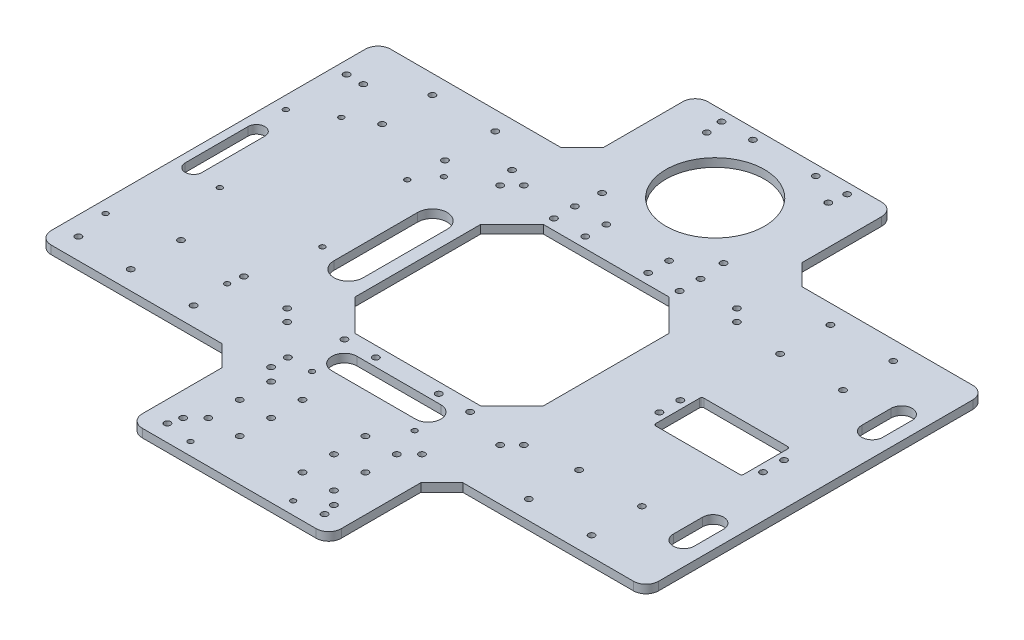
SolidWorks part; units mm, degrees
material "Thornel Mat VMA"
ref_plane "前视基准面" through (0, 0, 0) normal (0, 0, 1) x (1, 0, 0)
ref_plane "上视基准面" through (0, 0, 0) normal (0, 1, 0) x (1, 0, 0)
ref_plane "右视基准面" through (0, 0, 0) normal (1, 0, 0) x (0, 0, -1)
other "Configuration Table"
sketch "草图1" plane through (0, 0, 0) normal (0, 1, 0) x (1, 0, 0)
  line L0 (0, 0) -> (0, 135) construction
  line L1 (-145, -135) -> (145, -135)
  line L2 (-145, -135) -> (-145, 135)
  line L3 (-145, 135) -> (145, 135)
  line L4 (145, -135) -> (145, 135)
  line L5 (-145, -135) -> (145, 135) construction
  line L6 (-145, 135) -> (145, -135) construction
  line L7 (0, 0) -> (145, 0) construction
  line L8 (-47.5, 135) -> (-47.5, 81)
  line L9 (-47.5, 81) -> (-145, 81)
  line L10 (47.5, 81) -> (145, 81)
  line L11 (47.5, 135) -> (47.5, 81)
  line L12 (47.5, -81) -> (145, -81)
  line L13 (47.5, -135) -> (47.5, -81)
  line L14 (-47.5, -81) -> (-145, -81)
  line L15 (-47.5, -135) -> (-47.5, -81)
  point P0 (0, 0)
  dimension "D1" = 290
  dimension "D2" = 270
  dimension "D3" = 162
  dimension "D4" = 95
extrude "凸台-拉伸1" add sketch "草图1" along normal blind 4 contours L15 L1 L13 L12 L4 L10 L11 L3 L8 L9 L2 L14
sketch "草图2" plane through (0, 4, 0) normal (0, 1, 0) x (1, 0, 0)
  line L0 (0, 0) -> (145, 0) construction
  line L1 (145, -81) -> (145, 81) construction
  line L2 (0, 0) -> (0, 135) construction
  line L3 (-47.5, 135) -> (47.5, 135) construction
  line L4 (47.5, 81) -> (145, 81) construction
  circle A0 centre (110, 72) radius 1.5
  circle A1 centre (80, 72) radius 1.5
  circle A2 centre (80, 48) radius 1.5
  circle A3 centre (110, 48) radius 1.5
  circle A4 centre (110, -48) radius 1.5
  circle A5 centre (110, -72) radius 1.5
  circle A6 centre (80, -48) radius 1.5
  circle A7 centre (80, -72) radius 1.5
  circle A8 centre (-80, -72) radius 1.5
  circle A9 centre (-80, -48) radius 1.5
  circle A10 centre (-110, -72) radius 1.5
  circle A11 centre (-110, -48) radius 1.5
  circle A12 centre (-110, 48) radius 1.5
  circle A13 centre (-80, 48) radius 1.5
  circle A14 centre (-80, 72) radius 1.5
  circle A15 centre (-110, 72) radius 1.5
  dimension "D1" = 3
  dimension "D2" = 3
  dimension "D3" = 3
  dimension "D4" = 3
  dimension "D11" = 80
  dimension "D12" = 9
  dimension "D5" = 24
  dimension "D6" = 24
  dimension "D7" = 30
  dimension "D8" = 30
  dimension "D9" = 80
  dimension "D10" = 9
extrude "切除-拉伸1" cut sketch "草图2" against normal blind 4
sketch "草图3" plane through (0, 4, 0) normal (0, 1, 0) x (1, 0, 0)
  line L0 (0, 0) -> (0, 110.5115) construction
  line L1 (0, 0) -> (145, 0) construction
  line L2 (145, -81) -> (145, 81) construction
  line L3 (-86.4083, 97) -> (86.4083, 97) construction
  line L4 (0, 0) -> (0, 108.4938) construction
  line L7 (0, 0) -> (0, -114.288) construction
  circle A5 centre (0, 97) radius 23.5
  circle A33 centre (29, 122) radius 1.5
  circle A34 centre (29, 72) radius 1.5
  circle A35 centre (-29, 72) radius 1.5
  circle A36 centre (-29, 122) radius 1.5
  point P13 (0, 97)
  dimension "D2" = 97
  dimension "D6" = 47
  dimension "D12" = 25
  dimension "D8" = 3
  dimension "D5" = 0
  dimension "D9" = 29
extrude "切除-拉伸2" cut sketch "草图3" against normal blind 4
sketch "草图4" plane through (0, 4, 0) normal (0, 1, 0) x (1, 0, 0)
  line L1 (-45, -45) -> (45, -45)
  line L2 (-45, -45) -> (-45, 45)
  line L3 (-45, 45) -> (45, 45)
  line L4 (45, -45) -> (45, 45)
  line L5 (-45, -45) -> (45, 45) construction
  line L6 (-45, 45) -> (45, -45) construction
  point P0 (0, 0)
  dimension "D1" = 90
  dimension "D2" = 90
extrude "切除-拉伸3" cut sketch "草图4" against normal blind 4
fillet "圆角3" radius 6 8 edges at (-47.5, 2, -135) (47.5, 2, -135) (145, 2, -81) (145, 2, 81) (-47.5, 2, 135) (47.5, 2, 135) (-145, 2, 81) (-145, 2, -81)
chamfer "倒角1" distance 10 angle 45 4 edges at (47.5, 2, 81) (-47.5, 2, 81) (47.5, 2, -81) (-47.5, 2, -81)
sketch "草图7" plane through (0, 4, 0) normal (0, 1, 0) x (1, 0, 0)
  line L0 (0, 0) -> (0, 142.9478) construction
  line L1 (0, 0) -> (-184.5222, 0) construction
  line L2 (-137, -15) -> (-137, 15) construction
  line L5 (-58, -20) -> (-58, 20) construction
  line L6 (-65, -20) -> (-65, 20)
  line L7 (-51, -20) -> (-51, 20)
  line L8 (0, 0) -> (165.4514, 0) construction
  line L14 (-110, 0) -> (-110, 75.2826) construction
  line L15 (134, 38) -> (134, 52) construction
  line L33 (-141, -15) -> (-141, 15)
  line L34 (-133, -15) -> (-133, 15)
  line L35 (63, 0) -> (63, 55.2292) construction
  line L36 (0, -15) -> (172.3256, -15) construction
  line L38 (129, 38) -> (129, 52)
  line L39 (139, 38) -> (139, 52)
  line L40 (134, -38) -> (134, -52) construction
  line L41 (129, -38) -> (129, -52)
  line L42 (139, -38) -> (139, -52)
  arc A2 (-65, -20) -> (-51, -20) centre (-58, -20) ccw
  arc A3 (-51, 20) -> (-65, 20) centre (-58, 20) ccw
  arc A34 (-141, -15) -> (-133, -15) centre (-137, -15) ccw
  arc A35 (-133, 15) -> (-141, 15) centre (-137, 15) ccw
  arc A56 (129, 38) -> (139, 38) centre (134, 38) ccw
  arc A57 (139, 52) -> (129, 52) centre (134, 52) ccw
  arc A58 (129, -38) -> (139, -38) centre (134, -38) cw
  arc A59 (139, -52) -> (129, -52) centre (134, -52) cw
  point P6 (-137, 0)
  point P13 (-58, 0)
  point P21 (134, 45)
  point P37 (134, -45)
  dimension "D2" = 30
  dimension "D5" = 7
  dimension "D8" = 5
  dimension "D10" = 45
  dimension "D9" = 134
  dimension "D3" = 4
  dimension "D23" = 15
  dimension "D1" = 14
  dimension "D4" = 40
  dimension "D6" = 58
  dimension "D7" = 110
  dimension "D20" = 133
  dimension "D24" = 63
extrude "切除-拉伸6" cut sketch "草图7" against normal blind 4
chamfer "倒角2" distance 15 angle 45 4 edges at (45, 2, 45) (-45, 2, 45) (45, 2, -45) (-45, 2, -45)
sketch "草图8" plane through (0, 4, 0) normal (0, 1, 0) x (1, 0, 0)
  line L0 (0, 0) -> (0, 168.9929) construction
  line L1 (0, 0) -> (-169.1558, 0) construction
  line L2 (-103, 0) -> (-103, 65.828) construction
  line L3 (-103, -6) -> (-155.6162, -6) construction
  line L4 (0, 0) -> (-184.1789, 0) construction
  line L5 (0, 0) -> (0, 73.477) construction
  line L6 (-57.5, 81) -> (-139, 81) construction
  circle A15 centre (-139, 60) radius 1.5
  circle A16 centre (-131, 60) radius 1.5
  dimension "D2" = 8
  dimension "D4" = 103
  dimension "D5" = 6
  dimension "D6" = 0
  dimension "D7" = 3
  dimension "D8" = 3
  dimension "D11" = 28
  dimension "D12" = 36
  dimension "D10" = 21
extrude "切除-拉伸7" cut sketch "草图8" against normal blind 4
sketch "草图9" plane through (0, 4, 0) normal (0, 1, 0) x (1, 0, 0)
  line L0 (0, 0) -> (0, 165.3902) construction
  line L1 (0, 0) -> (179.4814, 0) construction
  line L2 (50.8431, 56.5) -> (56.5, 50.8431) construction
  line L3 (-62.5, -62.5) -> (62.5, -62.5) construction
  line L4 (-62.5, -62.5) -> (-62.5, 62.5) construction
  line L5 (-62.5, 62.5) -> (62.5, 62.5) construction
  line L6 (62.5, -62.5) -> (62.5, 62.5) construction
  line L7 (-62.5, -62.5) -> (62.5, 62.5) construction
  line L8 (-62.5, 62.5) -> (62.5, -62.5) construction
  line L18 (-50.3018, -50.3018) -> (40.4104, 40.4104) construction
  line L23 (-50.8431, -50.8431) -> (45.8431, 45.8431) construction
  line L24 (-48.3431, 48.3431) -> (48.3431, -48.3431) construction
  line L29 (-52.5221, -52.5221) -> (52.5221, 52.5221) construction
  line L30 (-52.5221, 52.5221) -> (52.5221, -52.5221) construction
  circle A0 centre (50.8431, 56.5) radius 1.5
  circle A1 centre (56.5, 50.8431) radius 1.5
  circle A2 centre (56.5, -50.8431) radius 1.5
  circle A3 centre (50.8431, -56.5) radius 1.5
  circle A4 centre (-50.8431, -56.5) radius 1.5
  circle A5 centre (-56.5, -50.8431) radius 1.5
  circle A6 centre (-56.5, 50.8431) radius 1.5
  circle A7 centre (-50.8431, 56.5) radius 1.5
  circle A8 centre (-37.5, -127) radius 1.5
  circle A9 centre (37.5, -127) radius 1.5
  dimension "D3" = 3
  dimension "D4" = 3
  dimension "D6" = 8
  dimension "D9" = 3
  dimension "D11" = 127
  dimension "D1" = 125
  dimension "D2" = 125
  dimension "D5" = 45
  dimension "D7" = 6
  dimension "D8" = 6
  dimension "D10" = 37.5
extrude "切除-拉伸8" cut sketch "草图9" against normal blind 4
sketch "草图10" plane through (0, 4, 0) normal (0, 1, 0) x (1, 0, 0)
  line L0 (0, 0) -> (173.0266, 0) construction
  line L1 (0, 0) -> (0, 114.2255) construction
sketch "草图11" plane through (0, 4, 0) normal (0, 1, 0) x (1, 0, 0)
  line L0 (0, 0) -> (183.5565, 0) construction
  line L1 (0, 0) -> (0, -155.5612) construction
sketch "草图12" plane through (0, 4, 0) normal (0, 1, 0) x (1, 0, 0)
  line L0 (-20, -60) -> (20, -60) construction
  line L1 (0, 0) -> (0, -155.5612) construction
  line L2 (-20, -54) -> (20, -54)
  line L3 (-20, -66) -> (20, -66)
  line L4 (0, 0) -> (173.0266, 0) construction
  arc A0 (-20, -54) -> (-20, -66) centre (-20, -60) ccw
  arc A1 (20, -66) -> (20, -54) centre (20, -60) ccw
  point P4 (0, -60)
  dimension "D2" = 6
  dimension "D1" = 40
  dimension "D3" = 60
extrude "切除-拉伸9" cut sketch "草图12" against normal blind 10
sketch "草图14" plane through (0, 4, 0) normal (0, 1, 0) x (1, 0, 0)
  line L0 (0, 0) -> (0, -145.4864) construction
  line L1 (0, 0) -> (173.1076, 0) construction
  line L2 (0, -100) -> (89.1596, -100) construction
  circle A0 centre (36, -79) radius 1.5
  circle A1 centre (36, -121) radius 1.5
  circle A2 centre (-36, -121) radius 1.5
  circle A3 centre (-36, -79) radius 1.5
  circle A4 centre (-24.5, -71) radius 1.25
  circle A5 centre (24.5, -71) radius 1.25
  circle A6 centre (24.5, -129) radius 1.25
  circle A7 centre (-24.5, -129) radius 1.25
  dimension "D1" = 3
  dimension "D2" = 42
  dimension "D3" = 72
  dimension "D5" = 2.5
  dimension "D6" = 49
  dimension "D7" = 58
  dimension "D4" = 100
extrude "切除-拉伸10" cut sketch "草图14" against normal blind 10
sketch "草图15" plane through (0, 4, 0) normal (0, 1, 0) x (1, 0, 0)
  line L0 (0, 0) -> (175.5609, 0) construction
  line L1 (0, 0) -> (0, 158.0719) construction
  line L2 (100.11, 0) -> (100.11, 39.6302) construction
  line L3 (79.11, -11.5) -> (121.11, -11.5)
  line L4 (79.11, -11.5) -> (79.11, 11.5)
  line L5 (79.11, 11.5) -> (121.11, 11.5)
  line L6 (121.11, -11.5) -> (121.11, 11.5)
  line L7 (79.11, -11.5) -> (121.11, 11.5) construction
  line L8 (79.11, 11.5) -> (121.11, -11.5) construction
  line L9 (110, 0) -> (110, 79.3701) construction
  circle A0 centre (75.36, 5) radius 1.5
  circle A2 centre (75.36, -5) radius 1.5
  circle A4 centre (124.86, -5) radius 1.5
  circle A5 centre (124.86, 5) radius 1.5
  point P3 (100.11, 0)
  dimension "D3" = 10
  dimension "D4" = 3
  dimension "D5" = 49.5
  dimension "D1" = 42
  dimension "D2" = 23
  dimension "D6" = 9.89
  dimension "D7" = 110
extrude "切除-拉伸11" cut sketch "草图15" against normal blind 10
fillet "圆角4" radius 1 4 edges at (79.11, 2, 11.5) (121.11, 2, 11.5) (121.11, 2, -11.5) (79.11, 2, -11.5)
sketch "草图16" plane through (0, 4, 0) normal (0, 1, 0) x (1, 0, 0)
  line L0 (0, 12) -> (-202.0071, 12) construction
  line L1 (0, 12) -> (0, 203.0309) construction
  line L2 (-98, -2.3134) -> (-98, 98.9217) construction
  line L4 (0, 0) -> (0, 12) construction
  line L5 (0, 0) -> (-183.682, 0) construction
  circle A0 centre (-73.5, 41) radius 1.25
  circle A1 centre (-122.5, 41) radius 1.25
  circle A2 centre (-73.5, -17) radius 1.25
  circle A3 centre (-122.5, -17) radius 1.25
  dimension "D1" = 58
  dimension "D2" = 49
  dimension "D3" = 2.5
  dimension "D4" = 98
  dimension "D5" = 12
extrude "切除-拉伸12" cut sketch "草图16" against normal blind 10
sketch "草图19" plane through (0, 4, 0) normal (0, 1, 0) x (1, 0, 0)
  line L0 (0, 0) -> (-178.7427, 0) construction
  line L1 (0, 0) -> (0, 171.7177) construction
  line L2 (-98, -10.9053) -> (-98, 46.7773) construction
  line L3 (-98, -7.4) -> (-15.7423, -7.4) construction
  circle A0 centre (-65, 50) radius 1.5
  circle A1 centre (-131, 50) radius 1.5
  circle A2 centre (-65, -64.8) radius 1.5
  circle A3 centre (-131, -64.8) radius 1.5
  dimension "D1" = 3
  dimension "D2" = 114.8
  dimension "D3" = 66
  dimension "D4" = 98
  dimension "D5" = 7.4
sketch "草图20" plane through (0, 4, 0) normal (0, 1, 0) x (1, 0, 0)
  line L0 (0, 0) -> (0, 140.7476) construction
  line L1 (0, 0) -> (-188.6657, 0) construction
  circle A0 centre (-60, 60) radius 1.5
  dimension "D1" = 3
  dimension "D2" = 60
  dimension "D3" = 60
sketch "草图22" plane through (0, 4, 0) normal (0, 1, 0) x (1, 0, 0)
  line L0 (0, 0) -> (154.1719, 0) construction
  line L1 (61, 0) -> (61, 40.4074) construction
  circle A0 centre (73, 13) radius 1.5
  circle A1 centre (49, 13) radius 1.5
  circle A2 centre (73, -13) radius 1.5
  circle A3 centre (49, -13) radius 1.5
  dimension "D1" = 24
  dimension "D2" = 26
  dimension "D3" = 3
  dimension "D4" = 61
sketch "草图23" plane through (0, 4, 0) normal (0, 1, 0) x (1, 0, 0)
  line L0 (0, 0) -> (-194.1261, 0) construction
  line L1 (-110, 0) -> (-110, 133.2192) construction
  line L3 (0, 0) -> (0, 84.0673) construction
  line L4 (0, -12) -> (-198.9065, -12) construction
  circle A0 centre (-81, 31) radius 1.25
  circle A3 centre (-139, 31) radius 1.25
  circle A4 centre (-81, -55) radius 1.25
  circle A5 centre (-139, -55) radius 1.25
  dimension "D1" = 2.5
  dimension "D2" = 58
  dimension "D3" = 86
  dimension "D5" = 12
  dimension "D4" = 110
extrude "切除-拉伸14" cut sketch "草图23" against normal blind 10
sketch "草图24" plane through (0, 4, 0) normal (0, 1, 0) x (1, 0, 0)
  line L0 (0, 0) -> (-236.5327, 0) construction
  line L1 (0, 0) -> (0, -171.9197) construction
  line L2 (0, -96) -> (-165.3693, -96) construction
  line L3 (-86, 0) -> (-86, -158.0192) construction
  circle A0 centre (-136, -71) radius 1.5
  circle A1 centre (-36, -71) radius 1.5
  circle A2 centre (-36, -121) radius 1.5
  dimension "D1" = 3
  dimension "D2" = 100
  dimension "D3" = 50
  dimension "D4" = 96
  dimension "D5" = 86
extrude "切除-拉伸15" cut sketch "草图24" against normal blind 10
extrude "切除-拉伸16" cut sketch "草图20" against normal blind 10
sketch "草图25" plane through (0, 4, 0) normal (0, 1, 0) x (1, 0, 0)
  line L0 (0, 135) -> (0, -135)
  line L1 (-41.5, 135) -> (41.5, 135) construction
  line L2 (-41.5, -135) -> (41.5, -135) construction
sketch "草图26" plane through (0, 4, 0) normal (0, 1, 0) x (1, 0, 0)
  line L0 (0, 135) -> (0, -135) construction
  line L1 (-30, -45) -> (30, -45) construction
  line L2 (-41.5, -135) -> (41.5, -135) construction
  line L3 (-30, -50) -> (15, -50) construction
  line L4 (30, 45) -> (-30, 45) construction
  line L5 (-30, 50) -> (-15, 50) construction
  line L6 (-30, 50) -> (15, 50) construction
  line L7 (-41.5, 135) -> (41.5, 135) construction
  circle A0 centre (-30, -115) radius 1.5
  circle A1 centre (-30, -100) radius 1.5
  circle A2 centre (-15, -100) radius 1.5
  circle A3 centre (-15, -115) radius 1.5
  circle A4 centre (15, -115) radius 1.5
  circle A5 centre (30, -115) radius 1.5
  circle A6 centre (15, -100) radius 1.5
  circle A7 centre (30, -100) radius 1.5
  circle A8 centre (-30, -85) radius 1.5
  circle A9 centre (-15, -85) radius 1.5
  circle A10 centre (15, -85) radius 1.5
  circle A11 centre (30, -85) radius 1.5
  circle A12 centre (-30, -50) radius 1.5
  circle A13 centre (-15, -50) radius 1.5
  circle A14 centre (15, -50) radius 1.5
  circle A15 centre (30, -50) radius 1.5
  circle A16 centre (-30, 50) radius 1.5
  circle A17 centre (-15, 50) radius 1.5
  circle A18 centre (15, 50) radius 1.5
  circle A19 centre (30, 50) radius 1.5
  circle A20 centre (-30, 60) radius 1.5
  circle A21 centre (-15, 60) radius 1.5
  circle A22 centre (15, 60) radius 1.5
  circle A23 centre (30, 60) radius 1.5
  circle A24 centre (-30, 130) radius 1.5
  circle A25 centre (-15, 130) radius 1.5
  circle A26 centre (15, 130) radius 1.5
  circle A27 centre (30, 130) radius 1.5
  dimension "D1" = 3
  dimension "D7" = 3
  dimension "D12" = 5
  dimension "D18" = 3
  dimension "D2" = 30
  dimension "D3" = 20
  dimension "D8" = 5
  dimension "D11" = 45
  dimension "D14" = 15
  dimension "D16" = 45
  dimension "D19" = 5
  dimension "D4" = 2
  dimension "D5" = 2
  dimension "D6" = 3
  dimension "D9" = 2
  dimension "D10" = 2
  dimension "D13" = 2
  dimension "D15" = 2
  dimension "D17" = 2
  dimension "D20" = 2
  dimension "D21" = 2
extrude "切除-拉伸17" cut sketch "草图26" against normal blind 10
